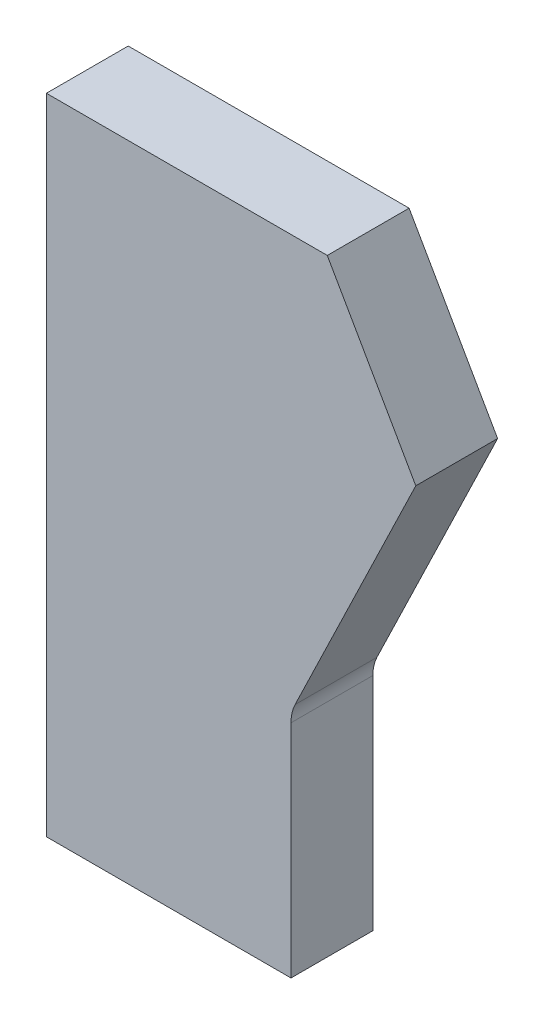
SolidWorks part; units mm, degrees
ref_plane "Front Plane" through (0, 0, 0) normal (0, 0, 1) x (1, 0, 0)
ref_plane "Top Plane" through (0, 0, 0) normal (0, 1, 0) x (1, 0, 0)
ref_plane "Right Plane" through (0, 0, 0) normal (1, 0, 0) x (0, 0, -1)
sketch "Sketch2" plane through (0, 0, 0) normal (0, 0, 1) x (1, 0, 0)
  line L0 (0, 0) -> (75.9298, 0)
  line L1 (75.9298, 0) -> (75.9298, 68.6086)
  line L2 (77.1945, 74.1335) -> (114.6635, 151.6855)
  line L3 (114.6635, 151.6855) -> (87.1896, 199.8775)
  line L4 (87.1896, 199.8775) -> (0, 199.8775)
  line L5 (0, 199.8775) -> (0, 0)
  arc A0 (75.9298, 68.6086) -> (77.1945, 74.1335) centre (88.6298, 68.6086) cw
  dimension "D1" = 12.7
extrude "Extrude1" add sketch "Sketch2" against normal blind 25.4
ref_plane "Plane2" through (0, 0, 0) normal (0, -1, 0) x (1, 0, 0)
sketch "Sketch3" plane through (0, 0, 0) normal (0, -1, 0) x (1, 0, 0)
  line L0 (0, 0) -> (75.9298, 0) construction
  line L1 (63.0521, 0) -> (75.9298, 0)
  line L2 (75.9298, 0) -> (75.9298, -3.6752)
  line L3 (75.9298, -25.4) -> (75.9298, 0) construction
  line L4 (75.9298, -3.6752) -> (79.7269, -3.6752)
  line L5 (79.7269, -3.6752) -> (79.7269, 0.2306)
  line L6 (79.7269, 0.2306) -> (87.9005, 0.2306)
  line L7 (87.9005, 0.2306) -> (87.9005, 3.2408)
  line L8 (86.8845, 4.2568) -> (73.9948, 4.2568)
  line L9 (72.9788, 3.2408) -> (72.9788, 2.6201)
  line L10 (71.9628, 1.6041) -> (64.0681, 1.6041)
  line L11 (63.0521, 0.5881) -> (63.0521, 0)
  arc A0 (72.9788, 2.6201) -> (71.9628, 1.6041) centre (71.9628, 2.6201) cw
  arc A1 (87.9005, 3.2408) -> (86.8845, 4.2568) centre (86.8845, 3.2408) ccw
  arc A2 (64.0681, 1.6041) -> (63.0521, 0.5881) centre (64.0681, 0.5881) ccw
  arc A3 (73.9948, 4.2568) -> (72.9788, 3.2408) centre (73.9948, 3.2408) ccw
  dimension "D1" = 1.016
  dimension "D2" = 1.016
